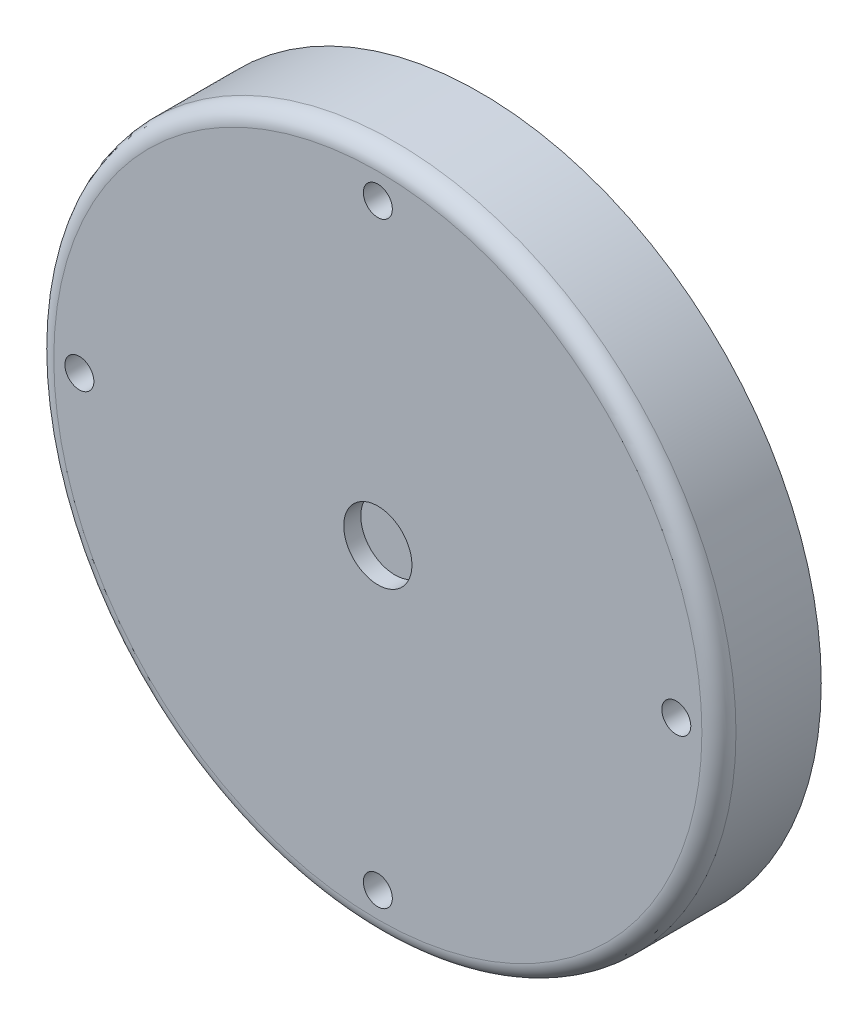
SolidWorks part; units mm, degrees
ref_plane "Płaszczyzna przednia" through (0, 0, 0) normal (0, 0, 1) x (1, 0, 0)
ref_plane "Płaszczyzna górna" through (0, 0, 0) normal (0, 1, 0) x (1, 0, 0)
ref_plane "Płaszczyzna prawa" through (0, 0, 0) normal (1, 0, 0) x (0, 0, -1)
sketch "Szkic1" plane through (0, 0, 0) normal (0, 0, 1) x (1, 0, 0)
  circle A0 centre (0, 0) radius 100
  dimension "D1" = 200
extrude "Dodanie-wyciągnięcie2" add sketch "Szkic1" along normal mid plane 10 contours A0
sketch "Szkic2" plane through (0, 0, -5) normal (0, 0, -1) x (-1, 0, 0)
  circle A0 centre (0, 0) radius 75
  circle A1 centre (0, 0) radius 100
  circle A2 centre (0, 0) radius 100
  dimension "D2" = 150
  dimension "D1" = 0
extrude "Dodanie-wyciągnięcie3" add sketch "Szkic2" along normal blind 20 contours A2 | A0
sketch "Szkic3" plane through (0, 0, 5) normal (0, 0, 1) x (1, 0, 0)
  line L0 (0, 119.0421) -> (0, -131.3818) construction
  line L1 (-135.0111, 0) -> (113.961, 0) construction
  circle A0 centre (0, 0) radius 70
  circle A1 centre (0, 0) radius 100
  circle A2 centre (0, 0) radius 100
  circle A8 centre (0, 0) radius 87.5
  circle A9 centre (87.5, 0) radius 4.25
  circle A10 centre (0, 87.5) radius 4.25
  circle A11 centre (0, -87.5) radius 4.25
  circle A12 centre (-87.5, 0) radius 4.25
  dimension "D2" = 12.5
  dimension "8,5" = 8.5
  dimension "D1" = 0
fillet "Zaokrąglenie1" radius 5 1 edges at (100, 0, 5)
sketch "Szkic4" plane through (0, 0, 5) normal (0, 0, 1) x (1, 0, 0)
  circle A0 centre (0, 0) radius 10
  dimension "D1" = 20
extrude "Wytnij-wyciągnięcie2" cut sketch "Szkic4" against normal blind 5 contours A0
extrude "Wytnij-wyciągnięcie3" cut sketch "Szkic3" against normal through all both and the other way through all contours A10 | A9 | A11 | A12
sketch "Szkic5" plane through (0, 0, 0) normal (0, 1, 0) x (1, 0, 0)
  line L0 (-96.75, -5) -> (-100, -5)
  line L1 (-105, 0) -> (-105, 25)
  line L2 (-105, 25) -> (-96.75, 25)
  line L3 (-96.75, 25) -> (-88.25, 25)
  line L4 (-88.25, 25) -> (-75, 25)
  line L5 (-75, 25) -> (77.5, 25)
  line L6 (77.5, 25) -> (88.25, 25)
  line L7 (88.25, 25) -> (96.75, 25)
  line L8 (96.75, 25) -> (105, 25)
  line L9 (105, 25) -> (105, 0)
  line L10 (100, -5) -> (96.75, -5)
  line L11 (96.75, -5) -> (88.25, -5)
  line L12 (88.25, -5) -> (10, -5)
  line L13 (10, -5) -> (-10, -5)
  line L14 (-10, -5) -> (-88.25, -5)
  line L15 (-88.25, -5) -> (-96.75, -5)
  line L16 (75, 5) -> (-75, 5) construction
  line L17 (75, 5) -> (-75, 5)
  line L18 (-75, 5) -> (-75, 25) construction
  line L19 (-75, 10) -> (-81, 10)
  line L20 (-81, 10) -> (-81, 16)
  line L21 (-81, 16) -> (-75, 16)
  line L22 (0, -17.3698) -> (0, 50.2477) construction
  line L23 (-75, 16) -> (-75, 10)
  arc A0 (-105, 0) -> (-100, -5) centre (-100, 0) ccw
  arc A1 (100, -5) -> (105, 0) centre (100, 0) ccw
  dimension "D1" = 6
  dimension "D2" = 6
  dimension "D3" = 5
revolve "Wycięcie-obrót1" cut sketch "Szkic5" angle 360 about L22
sketch "Szkic6" plane through (0, 0, -5) normal (0, 0, -1) x (-1, 0, 0)
  line L0 (0, 0) -> (0, 50000) construction
  line L1 (0, 0) -> (50000, 0) construction
  circle A9 centre (0, 0) radius 65 construction
  circle A13 centre (0, 0) radius 63 construction
  circle A14 centre (0, 0) radius 64 construction
  circle A15 centre (0, -64) radius 0.6
  circle A16 centre (-64, 0) radius 0.6
  circle A17 centre (0, 64) radius 0.6
  circle A18 centre (64, 0) radius 0.6
  dimension "D2" = 126
  dimension "D1" = 130
  dimension "D3" = 1
  dimension "D4" = 1.2
  dimension "D5" = 1.2
  dimension "D6" = 1.2
  dimension "D7" = 1.2
extrude "Wytnij-wyciągnięcie4" cut sketch "Szkic6" against normal blind 3
